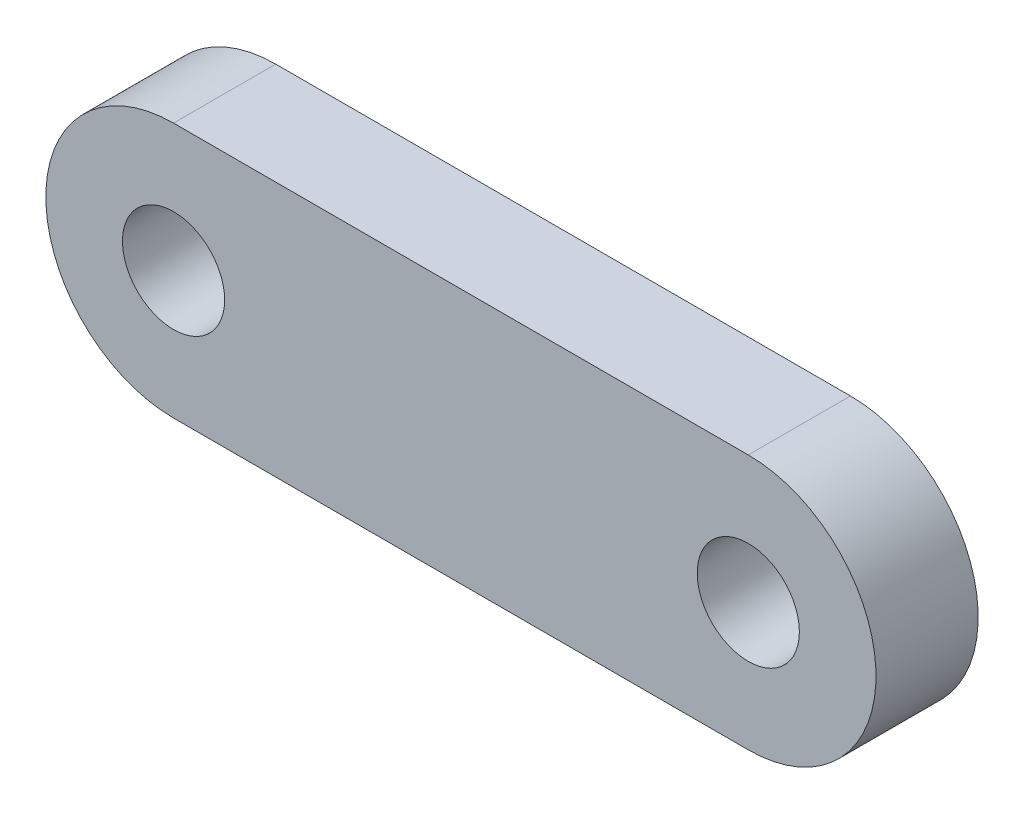
SolidWorks part; units mm, degrees
material "ABS"
ref_plane "Front Plane" through (0, 0, 0) normal (0, 0, 1) x (1, 0, 0)
ref_plane "Top Plane" through (0, 0, 0) normal (0, 1, 0) x (1, 0, 0)
ref_plane "Right Plane" through (0, 0, 0) normal (1, 0, 0) x (0, 0, -1)
sketch "Sketch1" plane through (0, 0, 0) normal (0, 0, 1) x (1, 0, 0)
  line L0 (0, 3.175) -> (14.2875, 3.175)
  line L1 (0, -3.175) -> (14.2875, -3.175)
  circle A0 centre (0, 0) radius 1.27
  circle A1 centre (0, 0) radius 3.175
  circle A2 centre (14.2875, 0) radius 1.27
  circle A3 centre (14.2875, 0) radius 3.175
  dimension "D1" = 2.54
  dimension "D2" = 6.35
  dimension "D3" = 14.2875
extrude "Boss-Extrude1" add sketch "Sketch1" along normal blind 2.54 contours A3 L0 A1 L1 | A1 A0 | A3 A2
